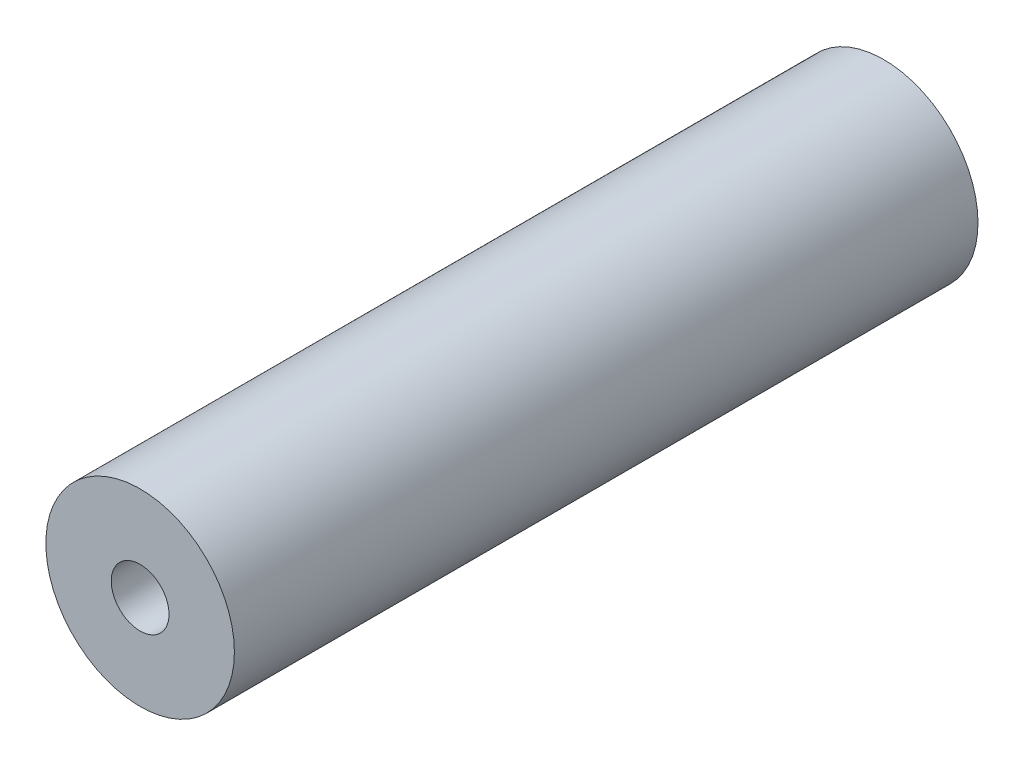
SolidWorks part; units mm, degrees
ref_plane "Front Plane" through (0, 0, 0) normal (0, 0, 1) x (1, 0, 0)
ref_plane "Top Plane" through (0, 0, 0) normal (0, 1, 0) x (1, 0, 0)
ref_plane "Right Plane" through (0, 0, 0) normal (1, 0, 0) x (0, 0, -1)
sketch "Sketch1" plane through (0, 0, 0) normal (0, 0, 1) x (1, 0, 0)
  circle A0 centre (0, 0) radius 8
  dimension "D1" = 16
extrude "Boss-Extrude1" add sketch "Sketch1" along normal blind 63.1
sketch "Sketch2" plane through (0, 0, 63.1) normal (0, 0, 1) x (1, 0, 0)
  circle A0 centre (0, 0) radius 2.45
  dimension "D1" = 4.9
extrude "Cut-Extrude1" cut sketch "Sketch2" against normal blind 10
sketch "Sketch3" plane through (0, 0, 0) normal (0, 0, -1) x (-1, 0, 0)
  circle A0 centre (0, 0) radius 2.45
  dimension "D1" = 4.9
extrude "Cut-Extrude2" cut sketch "Sketch3" against normal blind 10
